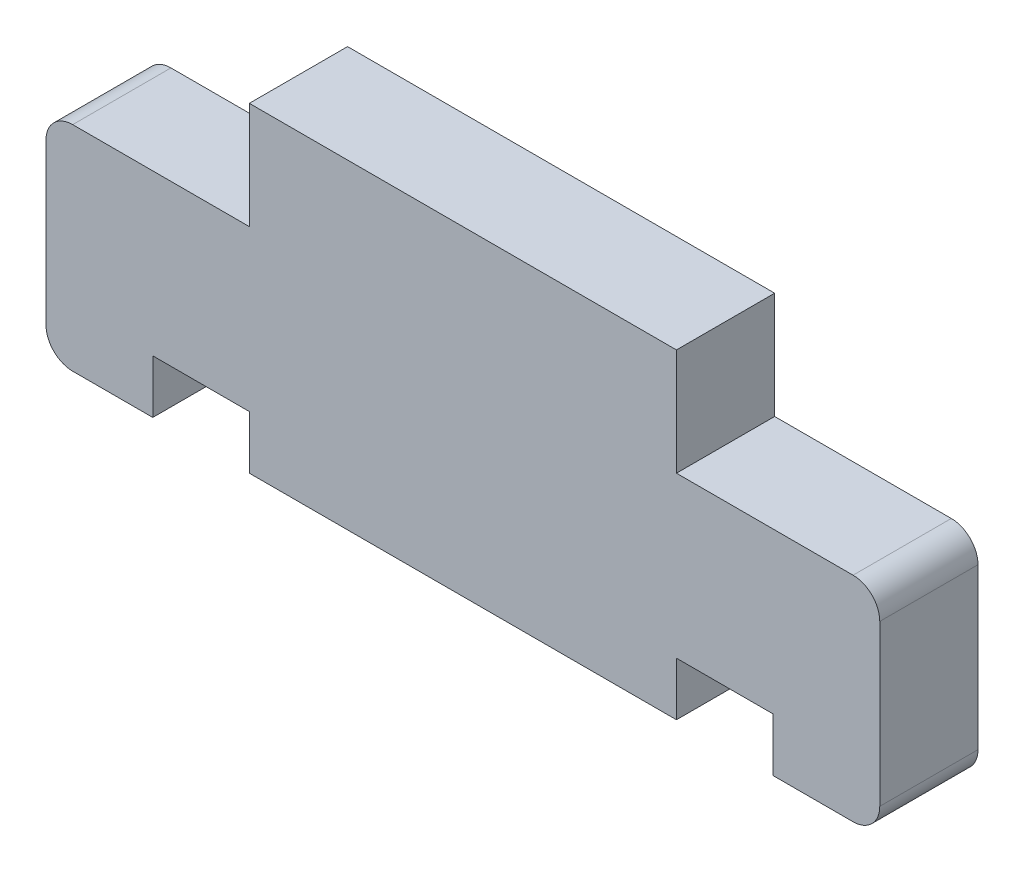
SolidWorks part; units mm, degrees
ref_plane "Front Plane" through (0, 0, 0) normal (0, 0, 1) x (1, 0, 0)
ref_plane "Top Plane" through (0, 0, 0) normal (0, 1, 0) x (1, 0, 0)
ref_plane "Right Plane" through (0, 0, 0) normal (1, 0, 0) x (0, 0, -1)
sketch "Sketch1" plane through (0, 0, 0) normal (0, 0, 1) x (1, 0, 0)
  line L0 (-12.7, -1.5875) -> (12.7, -1.5875) construction
  line L1 (12.7, -9.525) -> (-12.7, -9.525)
  line L2 (12.7, -9.525) -> (12.7, -6.35)
  line L3 (12.7, 9.525) -> (-12.7, 9.525)
  line L4 (-12.7, -9.525) -> (-12.7, -6.35)
  line L5 (12.7, -9.525) -> (-12.7, 9.525) construction
  line L6 (12.7, 9.525) -> (-12.7, -9.525) construction
  line L7 (12.7, 3.175) -> (12.7, 9.525)
  line L8 (18.442, -6.35) -> (12.7, -6.35)
  line L9 (0, 9.525) -> (0, -9.525) construction
  line L10 (18.442, 3.175) -> (12.7, 3.175)
  line L11 (-24.792, 3.175) -> (-18.442, -9.525) construction
  line L12 (18.442, -6.35) -> (12.7, 3.175) construction
  line L13 (18.442, 3.175) -> (12.7, -6.35) construction
  line L14 (24.792, -9.525) -> (18.442, -9.525)
  line L15 (24.792, -9.525) -> (24.792, 3.175)
  line L16 (24.792, 3.175) -> (18.442, 3.175)
  line L17 (18.442, -9.525) -> (18.442, -6.35)
  line L18 (24.792, -9.525) -> (18.442, 3.175) construction
  line L19 (24.792, 3.175) -> (18.442, -9.525) construction
  line L20 (-24.792, -9.525) -> (-18.442, 3.175) construction
  line L21 (-18.442, 3.175) -> (-12.7, -6.35) construction
  line L22 (-18.442, -6.35) -> (-12.7, 3.175) construction
  line L23 (-18.442, -9.525) -> (-18.442, -6.35)
  line L24 (-24.792, 3.175) -> (-18.442, 3.175)
  line L25 (-24.792, -9.525) -> (-24.792, 3.175)
  line L26 (-24.792, -9.525) -> (-18.442, -9.525)
  line L27 (-18.442, 3.175) -> (-12.7, 3.175)
  line L28 (-18.442, -6.35) -> (-12.7, -6.35)
  line L29 (-12.7, 3.175) -> (-12.7, 9.525)
  point P0 (0, 0)
  point P8 (15.571, -1.5875)
  point P13 (21.617, -3.175)
  point P26 (-21.617, -3.175)
  point P27 (-15.571, -1.5875)
  dimension "D1" = 25.4
  dimension "D2" = 19.05
  dimension "D3" = 5.742
  dimension "D4" = 9.525
  dimension "D5" = 7.9375
  dimension "D6" = 6.35
  dimension "D7" = 12.7
extrude "Boss-Extrude1" add sketch "Sketch1" along normal blind 5.842
fillet "Fillet1" radius 1.5875 4 edges at (-24.792, 3.175, 2.921) (-24.792, -9.525, 2.921) (24.792, -9.525, 2.921) (24.792, 3.175, 2.921)
